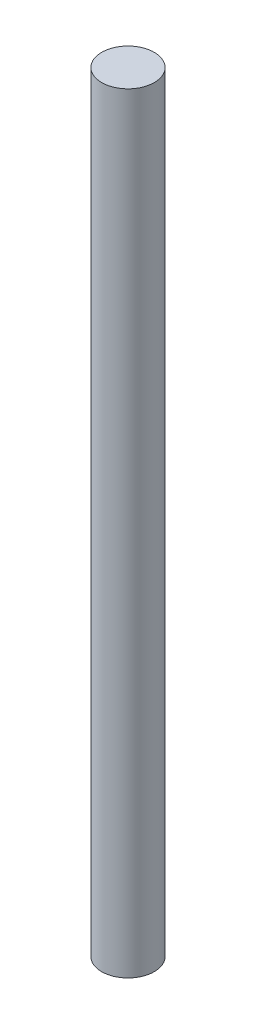
SolidWorks part; units mm, degrees
material "AISI 304"
ref_plane "Front Plane" through (0, 0, 0) normal (0, 0, 1) x (1, 0, 0)
ref_plane "Top Plane" through (0, 0, 0) normal (0, 1, 0) x (1, 0, 0)
ref_plane "Right Plane" through (0, 0, 0) normal (1, 0, 0) x (0, 0, -1)
sketch "Sketch1" plane through (0, 0, 0) normal (0, 1, 0) x (1, 0, 0)
  circle A0 centre (0, 0) radius 1.125
  dimension "D1" = 2.25
extrude "Boss-Extrude1" add sketch "Sketch1" along normal mid plane 33
